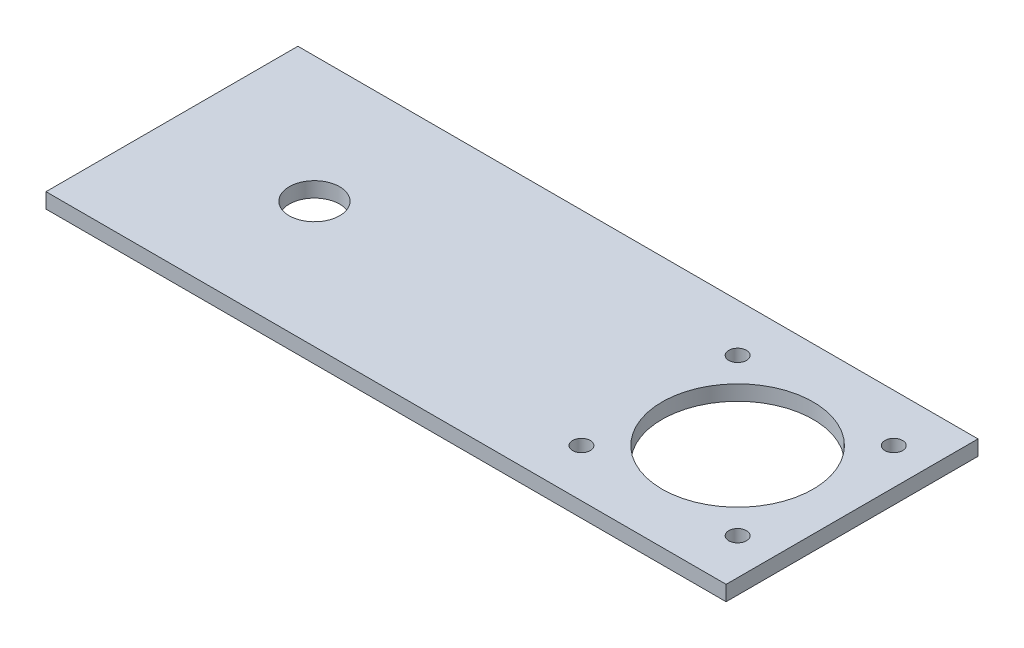
SolidWorks part; units mm, degrees
ref_plane "Front Plane" through (0, 0, 0) normal (0, 0, 1) x (1, 0, 0)
ref_plane "Top Plane" through (0, 0, 0) normal (0, 1, 0) x (1, 0, 0)
ref_plane "Right Plane" through (0, 0, 0) normal (1, 0, 0) x (0, 0, -1)
sketch "Sketch1" plane through (0, 0, 0) normal (0, 1, 0) x (1, 0, 0)
  line L0 (0, 25) -> (135, 25) construction
  line L1 (0, 0) -> (135, 0)
  line L2 (0, 0) -> (0, 50)
  line L3 (0, 50) -> (135, 50)
  line L4 (135, 0) -> (135, 50)
  line L5 (28.2843, -3.2843) -> (56.5685, 25) construction
  line L6 (28.2843, -3.2843) -> (0, 25) construction
  line L7 (56.5685, 25) -> (28.2843, 53.2843) construction
  line L8 (0, 25) -> (28.2843, 53.2843) construction
  line L9 (28.2843, -3.2843) -> (28.2843, 53.2843) construction
  line L10 (56.5685, 25) -> (0, 25) construction
  line L12 (96.7843, 9.5) -> (127.7843, 9.5) construction
  line L13 (96.7843, 9.5) -> (96.7843, 40.5) construction
  line L14 (96.7843, 40.5) -> (127.7843, 40.5) construction
  line L15 (127.7843, 9.5) -> (127.7843, 40.5) construction
  line L16 (96.7843, 9.5) -> (127.7843, 40.5) construction
  line L17 (96.7843, 40.5) -> (127.7843, 9.5) construction
  circle A0 centre (28.2843, 25) radius 5
  circle A1 centre (112.2843, 25) radius 15
  circle A2 centre (96.7843, 40.5) radius 1.75
  circle A3 centre (96.7843, 9.5) radius 1.75
  circle A4 centre (127.7843, 9.5) radius 1.75
  circle A5 centre (127.7843, 40.5) radius 1.75
  dimension "D4" = 10
  dimension "D7" = 3.5
  dimension "D8" = 30
  dimension "D1" = 84
  dimension "D2" = 50
  dimension "D3" = 40
  dimension "D5" = 135
  dimension "D6" = 31
extrude "Boss-Extrude1" add sketch "Sketch1" along normal blind 3 contours L3 L4 L1 L2
